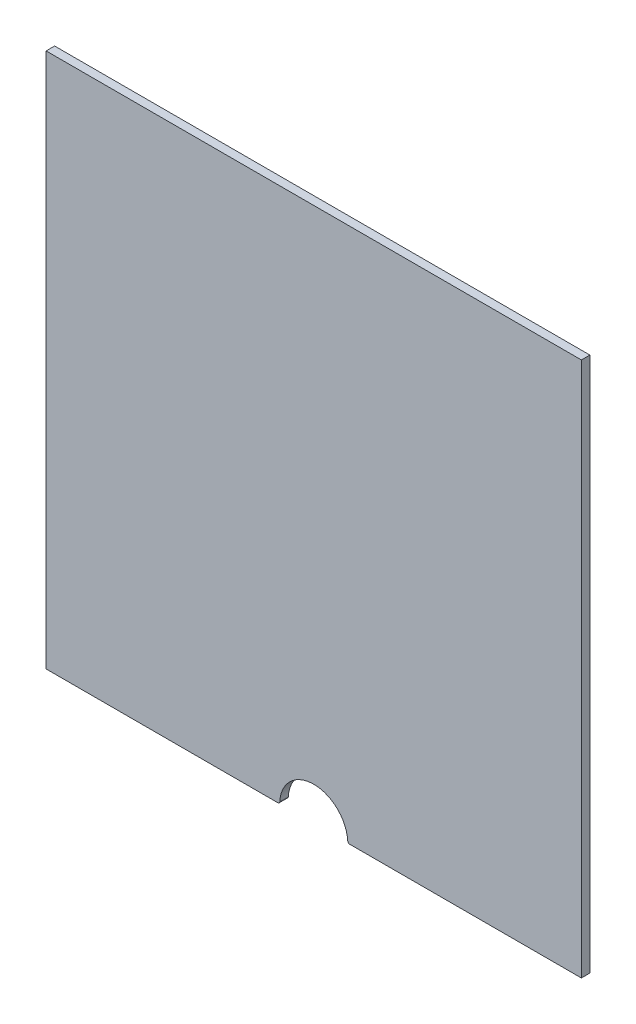
SolidWorks part; units mm, degrees
material "PVC Rigid"
ref_plane "Front Plane" through (0, 0, 0) normal (0, 0, 1) x (1, 0, 0)
ref_plane "Top Plane" through (0, 0, 0) normal (0, 1, 0) x (1, 0, 0)
ref_plane "Right Plane" through (0, 0, 0) normal (1, 0, 0) x (0, 0, -1)
sketch "Sketch1" plane through (0, 0, 0) normal (0, 0, 1) x (1, 0, 0)
  line L1 (0, 0) -> (200, 0)
  line L2 (0, 0) -> (0, 200)
  line L3 (0, 200) -> (200, 200)
  line L4 (200, 0) -> (200, 200)
  dimension "D1" = 200
extrude "Boss-Extrude1" add sketch "Sketch1" along normal blind 3.175
sketch "Sketch5" plane through (0, 0, 3.175) normal (0, 0, 1) x (1, 0, 0)
  line L0 (200, 0) -> (200, 200) construction
  line L1 (0, 0) -> (200, 0) construction
  line L2 (0, 200) -> (0, 0) construction
  line L3 (200, 200) -> (0, 200) construction
  line L4 (200, 0) -> (200, 200)
  line L5 (0, 0) -> (200, 0)
  line L6 (0, 200) -> (0, 0)
  line L7 (200, 200) -> (0, 200)
  line L8 (199.9492, 0.0508) -> (199.9492, 199.9492)
  line L9 (199.9492, 199.9492) -> (0.0508, 199.9492)
  line L10 (0.0508, 199.9492) -> (0.0508, 0.0508)
  line L11 (0.0508, 0.0508) -> (199.9492, 0.0508)
  dimension "D1" = 0.0508
extrude "Cut-Extrude2" cut sketch "Sketch5" against normal through all
sketch "Sketch2" plane through (0, 0, 3.175) normal (0, 0, 1) x (1, 0, 0)
  line L1 (87.3, 0.0508) -> (112.7, 0.0508)
  line L2 (0.0508, 0.0508) -> (199.9492, 0.0508) construction
  line L3 (100, 199.9492) -> (100, 0.0508) construction
  line L4 (199.9492, 199.9492) -> (0.0508, 199.9492) construction
  arc A0 (112.7, 0.0508) -> (87.3, 0.0508) centre (100, 0.0508) ccw
  dimension "D1" = 25.4
extrude "Cut-Extrude1" cut sketch "Sketch2" against normal blind 3.175
fillet "Fillet1" radius 0.7937 2 edges at (87.3, 0.0508, 1.5875) (112.7, 0.0508, 1.5875)
sketch "Sketch6" plane through (0, 0, 3.175) normal (0, 0, 1) x (1, 0, 0)
  line L0 (0.0508, 199.9492) -> (0.0508, 0.0508) construction
  line L1 (0.0508, 0.0508) -> (86.5296, 0.0508) construction
  circle A0 centre (2.0828, 2.0828) radius 0.7938
  dimension "D1" = 1.5875
  dimension "D2" = 2.032
  dimension "D3" = 2.032
extrude "Cut-Extrude3" [suppressed] cut sketch "Sketch6" against normal blind 1.27
pattern_linear "LPattern1" [suppressed] count 4 spacing 2.54
